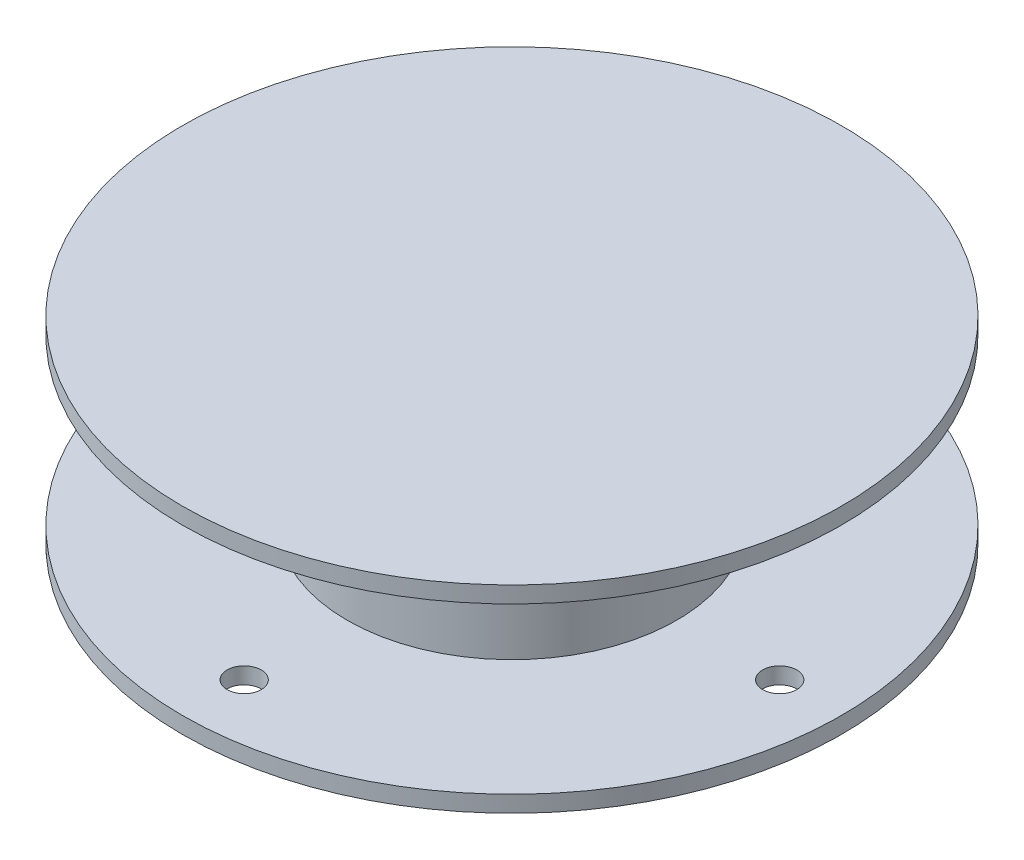
SolidWorks part; units mm, degrees
ref_plane "Front Plane" through (0, 0, 0) normal (0, 0, 1) x (1, 0, 0)
ref_plane "Top Plane" through (0, 0, 0) normal (0, 1, 0) x (1, 0, 0)
ref_plane "Right Plane" through (0, 0, 0) normal (1, 0, 0) x (0, 0, -1)
sketch "Sketch1" plane through (0, 0, 0) normal (0, 1, 0) x (1, 0, 0)
  circle A0 centre (0, 0) radius 40
  dimension "D1" = 80
extrude "Boss-Extrude1" add sketch "Sketch1" along normal blind 2
sketch "Sketch2" plane through (0, 2, 0) normal (0, 1, 0) x (1, 0, 0)
  circle A0 centre (0, 0) radius 20
  dimension "D1" = 40
extrude "Boss-Extrude2" add sketch "Sketch2" along normal blind 10
mirror "Mirror1" about plane through (0, 12, 0) normal (0, 1, 0) of "Boss-Extrude1", "Boss-Extrude2"
sketch "Sketch3" plane through (0, 0, 0) normal (0, -1, 0) x (1, 0, 0)
  circle A0 centre (0, 0) radius 32.5 construction
  circle A1 centre (0, 32.5) radius 2.0736
  circle A2 centre (32.5, 0) radius 2.0736
  circle A3 centre (0, -32.5) radius 2.0736
  circle A4 centre (-32.5, 0) radius 2.0736
  dimension "D1" = 65
  dimension "D2" = 4.1472
  dimension "D3" = 4
extrude "Cut-Extrude1" cut sketch "Sketch3" against normal up to next
